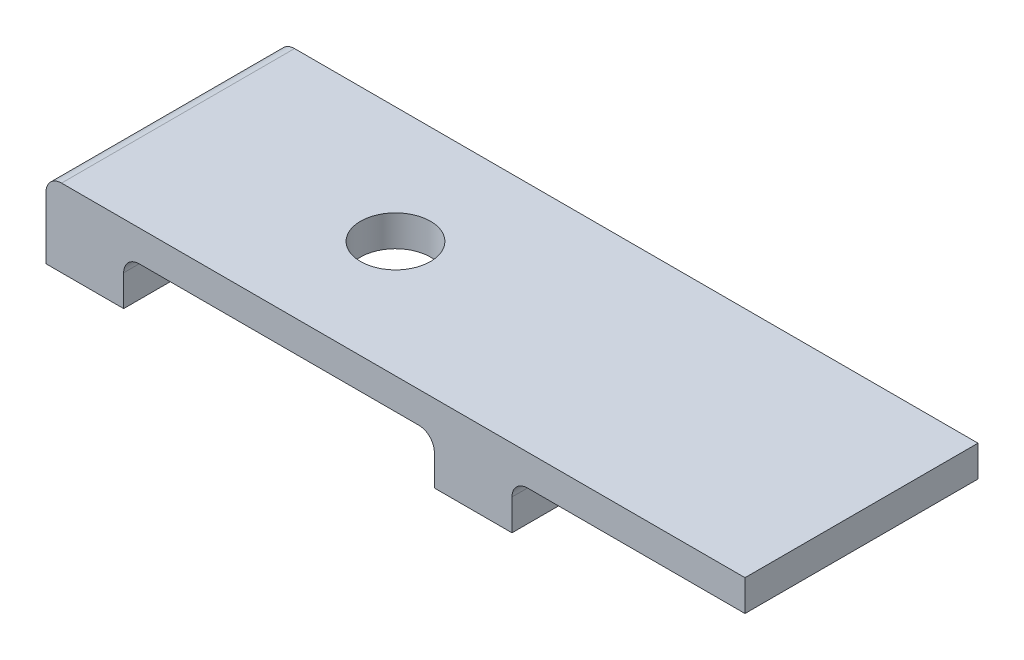
SolidWorks part; units mm, degrees
ref_plane "Front Plane" through (0, 0, 0) normal (0, 0, 1) x (1, 0, 0)
ref_plane "Top Plane" through (0, 0, 0) normal (0, 1, 0) x (1, 0, 0)
ref_plane "Right Plane" through (0, 0, 0) normal (1, 0, 0) x (0, 0, -1)
sketch "Sketch1" plane through (0, 0, 0) normal (0, 0, 1) x (1, 0, 0)
  line L0 (-1000, 0) -> (49000, 0) construction
  line L1 (0, -1000) -> (0, 49000) construction
  line L2 (0, 0) -> (45, 0)
  line L3 (0, 0) -> (0, -5)
  line L4 (0, -5) -> (5, -5)
  line L5 (5, -5) -> (5, -2)
  line L6 (5, -2) -> (25, -2)
  line L7 (25, -2) -> (25, -5)
  line L8 (25, -5) -> (30, -5)
  line L9 (30, -5) -> (30, -2)
  line L10 (30, -2) -> (45, -2)
  line L11 (45, -2) -> (45, 0)
  dimension "D1" = 45
  dimension "D2" = 5
  dimension "D3" = 5
  dimension "D4" = 3
  dimension "D5" = 20
  dimension "D6" = 3
  dimension "D7" = 5
  dimension "D8" = 3
  dimension "D9" = 15
extrude "Boss-Extrude1" add sketch "Sketch1" along normal blind 15
fillet "Fillet1" radius 1 1 edges at (0, 0, 7.5)
fillet "Fillet2" radius 1 1 edges at (5, -2, 7.5)
fillet "Fillet3" radius 1 1 edges at (25, -2, 7.5)
fillet "Fillet4" radius 1 1 edges at (30, -2, 7.5)
sketch "Sketch2" plane through (0, 0, 0) normal (0, 1, 0) x (1, 0, 0)
  line L0 (45, 0) -> (1, 0) construction
  line L1 (1, 0) -> (1, -15) construction
  circle A0 centre (15, -7.5) radius 2.25
  dimension "D3" = 4.5
  dimension "D1" = 7.5
  dimension "D2" = 14
extrude "Cut-Extrude1" cut sketch "Sketch2" against normal blind 5 contours A0
